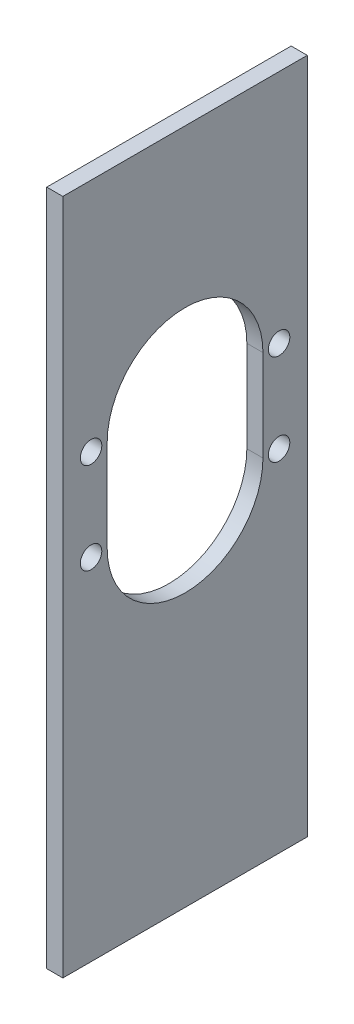
SolidWorks part; units mm, degrees
ref_plane "Front Plane" through (0, 0, 0) normal (0, 0, 1) x (1, 0, 0)
ref_plane "Top Plane" through (0, 0, 0) normal (0, 1, 0) x (1, 0, 0)
ref_plane "Right Plane" through (0, 0, 0) normal (1, 0, 0) x (0, 0, -1)
sketch "Sketch1" plane through (0, 0, 0) normal (1, 0, 0) x (0, 0, -1)
  line L0 (2.75, -52.3) -> (42.75, -52.3) construction
  line L5 (0, 0) -> (45.5, 0)
  line L10 (0, 0) -> (0, -126)
  line L11 (0, -126) -> (45.5, -126)
  line L12 (45.5, 0) -> (45.5, -126)
  line L13 (2.75, -13) -> (42.75, -13) construction
  line L14 (2.75, -13) -> (2.75, -113) construction
  line L15 (2.75, -113) -> (42.75, -113) construction
  line L16 (42.75, -13) -> (42.75, -113) construction
  line L17 (22.75, 0) -> (22.75, -126) construction
  line L18 (5.25, -43.8) -> (40.25, -43.8) construction
  line L19 (8.25, -60.8) -> (8.25, -43.8)
  line L20 (37.25, -60.8) -> (37.25, -43.8)
  circle A0 centre (5.25, -60.8) radius 2
  circle A1 centre (40.25, -60.8) radius 2
  circle A3 centre (40.25, -43.8) radius 2
  circle A4 centre (5.25, -43.8) radius 2
  arc A6 (37.25, -60.8) -> (8.25, -60.8) centre (22.75, -60.8) cw
  arc A7 (37.25, -43.8) -> (8.25, -43.8) centre (22.75, -43.8) ccw
  point P9 (22.75, -13)
  point P10 (22.75, 0)
  point P11 (2.75, -63)
  point P12 (0, -63)
  point P27 (22.75, -43.8)
  dimension "D8" = 4
  dimension "D9" = 4
  dimension "D1" = 100
  dimension "D2" = 126
  dimension "D3" = 40
  dimension "D4" = 45.5
  dimension "D5" = 39.3
  dimension "D6" = 8.5
  dimension "D10" = 35
  dimension "D11" = 17.5
extrude "Boss-Extrude1" add sketch "Sketch1" along normal blind 3
